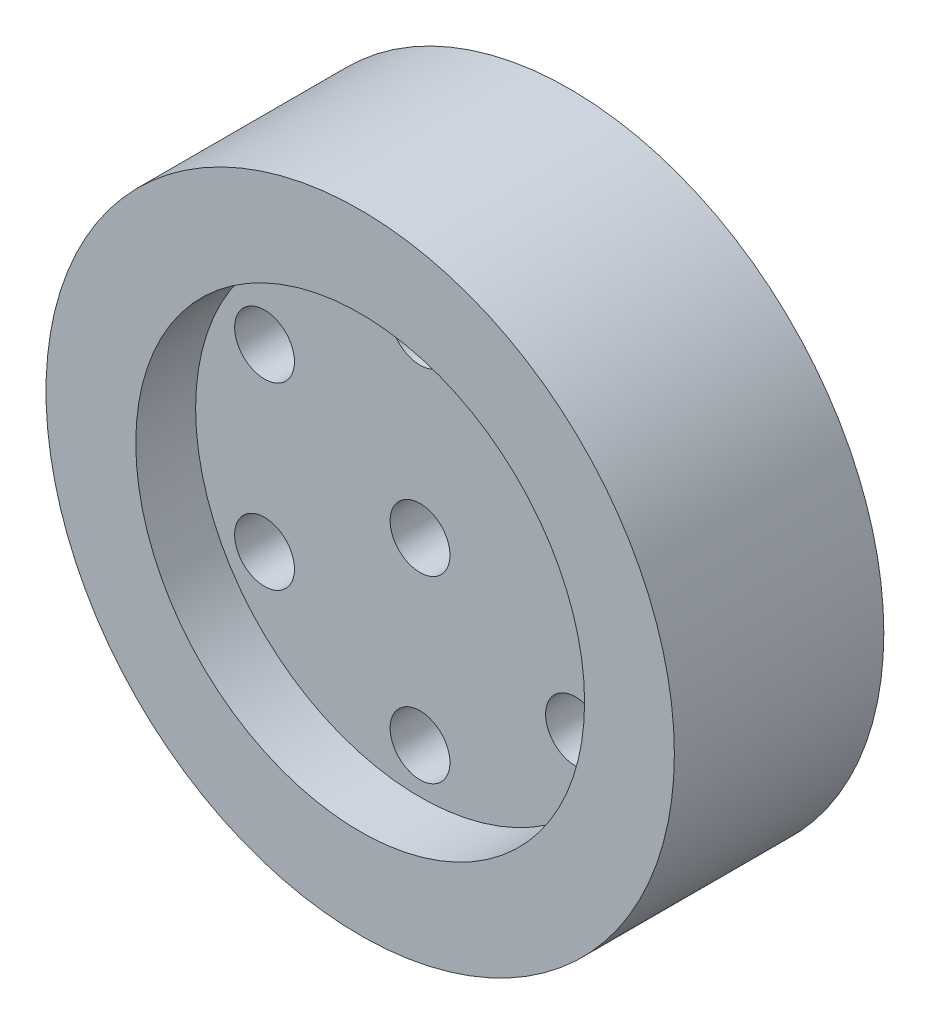
SolidWorks part; units mm, degrees
ref_plane "Front Plane" through (0, 0, 0) normal (0, 0, 1) x (1, 0, 0)
ref_plane "Top Plane" through (0, 0, 0) normal (0, 1, 0) x (1, 0, 0)
ref_plane "Right Plane" through (0, 0, 0) normal (1, 0, 0) x (0, 0, -1)
sketch "Sketch1" plane through (0, 0, 0) normal (0, 0, 1) x (1, 0, 0)
  circle A0 centre (0, 0) radius 21
  dimension "D1" = 42
extrude "Boss-Extrude1" add sketch "Sketch1" along normal mid plane 14
sketch "Sketch2" plane through (0, 0, 7) normal (0, 0, 1) x (1, 0, 0)
  circle A0 centre (0, 0) radius 15
  dimension "D1" = 30
extrude "Cut-Extrude1" cut sketch "Sketch2" against normal blind 4
sketch "Sketch3" plane through (0, 0, 3) normal (0, 0, 1) x (1, 0, 0)
  line L0 (0, 0) -> (0, 13.7868) construction
  circle A0 centre (0, 0) radius 12 construction
  circle A1 centre (0, 12) radius 2
  circle A2 centre (10.3923, 6) radius 2
  circle A3 centre (10.3923, -6) radius 2
  circle A4 centre (0, -12) radius 2
  circle A5 centre (-10.3923, -6) radius 2
  circle A6 centre (-10.3923, 6) radius 2
  point P19 (0, 0)
  dimension "D1" = 24
  dimension "D2" = 4
  dimension "D3" = 6
extrude "Cut-Extrude2" cut sketch "Sketch3" against normal through all
sketch "Sketch4" plane through (0, 0, -7) normal (0, 0, -1) x (-1, 0, 0)
  circle A0 centre (0, 0) radius 12 construction
  circle A3 centre (0, 0) radius 19
  dimension "D1" = 24
  dimension "D2" = 38
extrude "Cut-Extrude3" cut sketch "Sketch4" against normal blind 4
sketch "Sketch7" plane through (0, 0, -3) normal (0, 0, -1) x (-1, 0, 0)
  circle A0 centre (0, 0) radius 5
  dimension "D1" = 10
extrude "Boss-Extrude3" add sketch "Sketch7" along normal up to surface (4 mm away) up to face at (-19, 0, -7)
sketch "Sketch8" plane through (0, 0, -7) normal (0, 0, -1) x (-1, 0, 0)
  circle A0 centre (0, 0) radius 2
  dimension "D1" = 4
extrude "Cut-Extrude5" cut sketch "Sketch8" against normal through all
